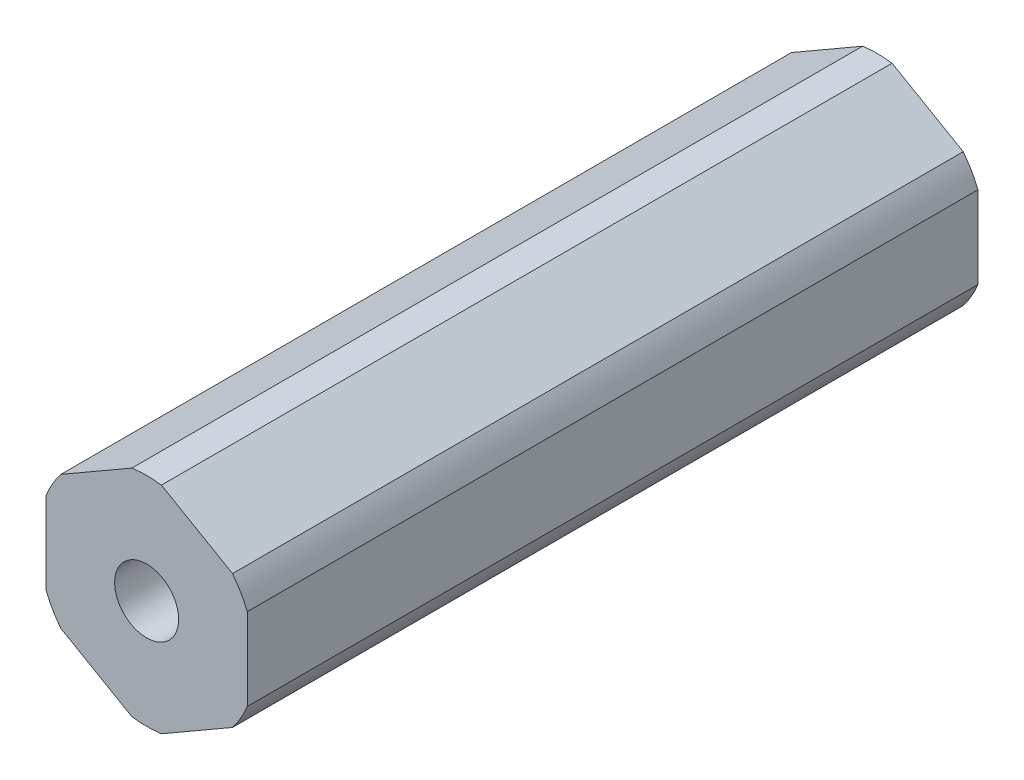
SolidWorks part; units mm, degrees
material "6061-T6 (SS)"
ref_plane "Front Plane" through (0, 0, 0) normal (0, 0, 1) x (1, 0, 0)
ref_plane "Top Plane" through (0, 0, 0) normal (0, 1, 0) x (1, 0, 0)
ref_plane "Right Plane" through (0, 0, 0) normal (1, 0, 0) x (0, 0, -1)
sketch "Sketch1" plane through (0, 0, 0) normal (0, 0, 1) x (1, 0, 0)
  line L1 (-0.9317, 6.7944) -> (-5.4183, 4.2041)
  line L2 (-6.35, 2.5903) -> (-6.35, -2.5903)
  line L3 (-5.4183, -4.2041) -> (-0.9317, -6.7944)
  line L4 (0.9317, -6.7944) -> (5.4183, -4.2041)
  line L5 (6.35, -2.5903) -> (6.35, 2.5903)
  line L6 (5.4183, 4.2041) -> (0.9317, 6.7944)
  circle A0 centre (0, 0) radius 6.35 construction
  arc A1 (-6.35, -2.5903) -> (-5.4183, -4.2041) centre (0, 0) ccw
  arc A2 (-0.9317, -6.7944) -> (0.9317, -6.7944) centre (0, 0) ccw
  arc A3 (5.4183, -4.2041) -> (6.35, -2.5903) centre (0, 0) ccw
  arc A4 (6.35, 2.5903) -> (5.4183, 4.2041) centre (0, 0) ccw
  arc A5 (0.9317, 6.7944) -> (-0.9317, 6.7944) centre (0, 0) ccw
  arc A6 (-5.4183, 4.2041) -> (-6.35, 2.5903) centre (0, 0) ccw
  dimension "D1" = 12.7
  dimension "D2" = 13.716
extrude "Boss-Extrude1" add sketch "Sketch1" along normal blind 46.101
sketch "Sketch2" plane through (0, 0, 46.101) normal (0, 0, 1) x (1, 0, 0)
  circle A0 centre (0, 0) radius 2.0193
  dimension "D1" = 4.0386
extrude "Cut-Extrude1" cut sketch "Sketch2" against normal through all
